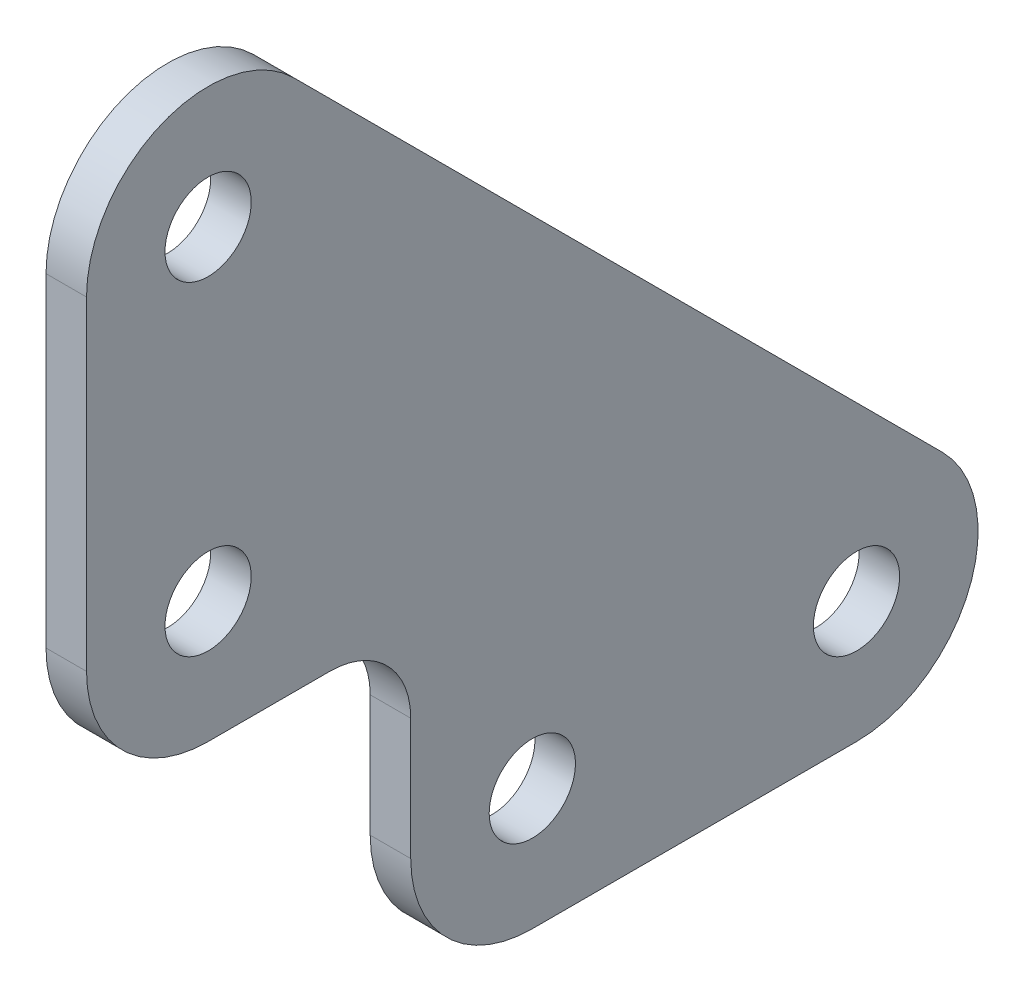
SolidWorks part; units mm, degrees
ref_plane "Front Plane" through (0, 0, 0) normal (0, 0, 1) x (1, 0, 0)
ref_plane "Top Plane" through (0, 0, 0) normal (0, 1, 0) x (1, 0, 0)
ref_plane "Right Plane" through (0, 0, 0) normal (1, 0, 0) x (0, 0, -1)
sketch "Sketch1" plane through (0, 0, 0) normal (1, 0, 0) x (0, 0, -1)
  line L46 (-1321.7401, 202.4398) -> (-1270.9401, 151.6398) construction
  line L47 (-1303.0753, 135.3796) -> (-1277.6753, 135.3796) construction
  line L48 (-1338.0003, 170.3046) -> (-1338.0003, 195.7046) construction
  line L52 (-1312.6003, 160.7796) -> (-1312.6003, 144.9046) construction
  line L53 (-1328.4753, 160.7796) -> (-1312.6003, 160.7796) construction
  line L54 (-1321.7401, 202.4398) -> (-1270.9401, 151.6398)
  line L55 (-1303.0753, 135.3796) -> (-1277.6753, 135.3796)
  line L56 (-1338.0003, 170.3046) -> (-1338.0003, 195.7046)
  line L60 (-1312.6003, 160.7796) -> (-1312.6003, 144.9046)
  line L61 (-1328.4753, 160.7796) -> (-1312.6003, 160.7796)
  circle A0 centre (-1328.4753, 170.3046) radius 9.525 construction
  arc A1 (-1338.0003, 170.3046) -> (-1328.4753, 160.7796) centre (-1328.4753, 170.3046) ccw
  circle A2 centre (-1328.4753, 195.7046) radius 9.525 construction
  circle A3 centre (-1277.6753, 144.9046) radius 9.525 construction
  circle A4 centre (-1303.0753, 144.9046) radius 9.525 construction
  arc A21 (-1321.7401, 202.4398) -> (-1338.0003, 195.7046) centre (-1328.4753, 195.7046) ccw
  arc A22 (-1277.6753, 135.3796) -> (-1270.9401, 151.6398) centre (-1277.6753, 144.9046) ccw
  arc A23 (-1312.6003, 144.9046) -> (-1303.0753, 135.3796) centre (-1303.0753, 144.9046) ccw
extrude "Boss-Extrude1" add sketch "Sketch1" against normal up to vertex from vertex
hole_wizard "1/4 Clearance Hole1" positions "Sketch2" profile "Sketch3" hole size "1/4" standard "ANSI Inch" end condition through all
sketch "Sketch2" plane through (92.8688, 0, 0) normal (-1, 0, 0) x (0, 0, 1)
  point P29 (1328.4753, 195.7046)
  point P31 (1328.4753, 170.3046)
  point P33 (1277.6753, 144.9046)
  point P35 (1303.0753, 144.9046)
sketch "Sketch3" plane through (92.8688, 195.7046, 1328.4753) normal (0, 1, 0) x (0, 0, 1)
  line L0 (0, 0) -> (0, 3.175)
  line L1 (0, 3.175) -> (3.3782, 3.175)
  line L2 (3.3782, 3.175) -> (3.3782, 0)
  line L5 (3.3782, 0) -> (0, 0)
  line L11 (0, -6.35) -> (0, 107.95) construction
  dimension "Thru Hole Dia." = 6.7564
  dimension "Thru Hole Depth" = 3.175
fillet "Fillet1" radius 6.35 1 edges at (94.4563, 160.7796, 1312.6003)
